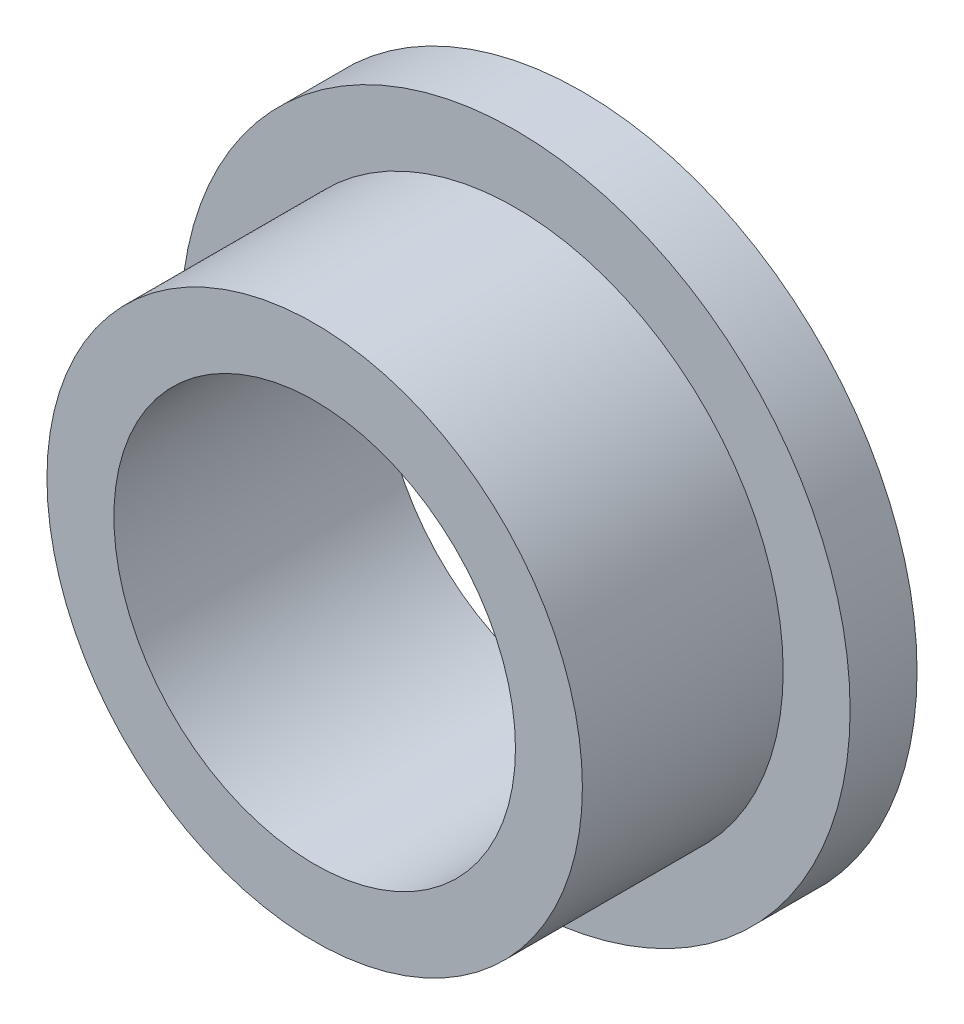
SolidWorks part; units mm, degrees
ref_plane "前视基准面" through (0, 0, 0) normal (0, 0, 1) x (1, 0, 0)
ref_plane "上视基准面" through (0, 0, 0) normal (0, 1, 0) x (1, 0, 0)
ref_plane "右视基准面" through (0, 0, 0) normal (1, 0, 0) x (0, 0, -1)
sketch "草图1" plane through (0, 0, 0) normal (1, 0, 0) x (0, 0, -1)
  line L0 (0, 0) -> (68.6406, 0) construction
  line L1 (0, 3) -> (4, 3)
  line L2 (4, 3) -> (4, 5)
  line L3 (4, 5) -> (3, 5)
  line L4 (3, 5) -> (3, 4)
  line L5 (3, 4) -> (0, 4)
  line L6 (0, 4) -> (0, 3)
  dimension "D1" = 3
  dimension "D2" = 1
  dimension "D3" = 1
  dimension "D4" = 2
  dimension "D5" = 3
revolve "旋转1" add sketch "草图1" angle 360 about L0
